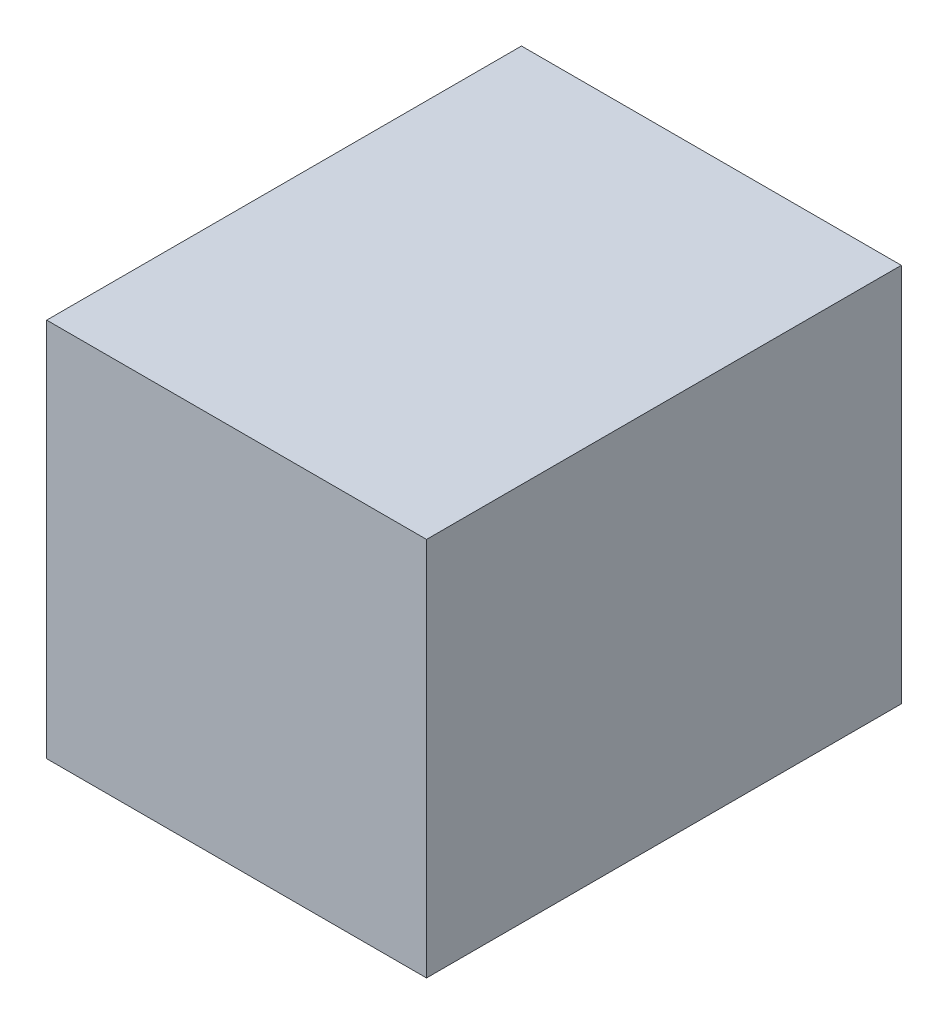
SolidWorks part; units mm, degrees
ref_plane "Front Plane" through (0, 0, 0) normal (0, 0, 1) x (1, 0, 0)
ref_plane "Top Plane" through (0, 0, 0) normal (0, 1, 0) x (1, 0, 0)
ref_plane "Right Plane" through (0, 0, 0) normal (1, 0, 0) x (0, 0, -1)
sketch "Sketch1" plane through (0, 0, 0) normal (0, 1, 0) x (1, 0, 0)
  line L1 (-10, 12.5) -> (10, 12.5)
  line L2 (-10, 12.5) -> (-10, -12.5)
  line L3 (-10, -12.5) -> (10, -12.5)
  line L4 (10, 12.5) -> (10, -12.5)
  line L5 (-10, 12.5) -> (10, -12.5) construction
  line L6 (-10, -12.5) -> (10, 12.5) construction
  point P0 (0, 0)
  dimension "D1" = 25
  dimension "D2" = 20
extrude "Boss-Extrude1" add sketch "Sketch1" along normal blind 20
